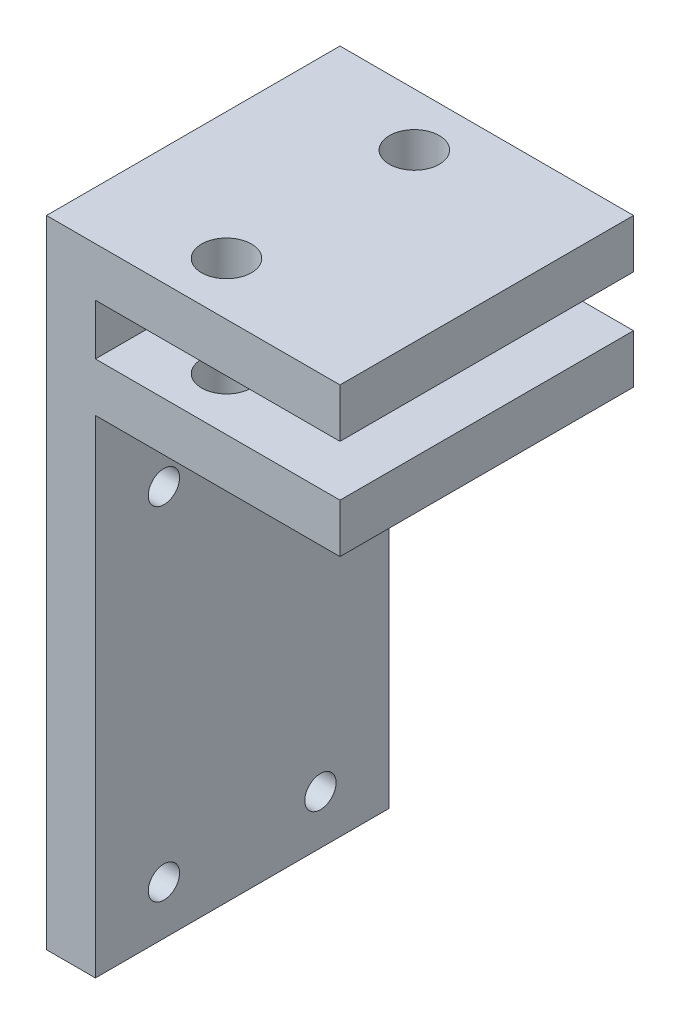
SolidWorks part; units mm, degrees
ref_plane "Front Plane" through (0, 0, 0) normal (0, 0, 1) x (1, 0, 0)
ref_plane "Top Plane" through (0, 0, 0) normal (0, 1, 0) x (1, 0, 0)
ref_plane "Right Plane" through (0, 0, 0) normal (1, 0, 0) x (0, 0, -1)
sketch "Sketch1" plane through (0, 0, 0) normal (0, 0, 1) x (1, 0, 0)
  line L0 (0, 0) -> (0, 5)
  line L1 (0, 5) -> (-30, 5)
  line L2 (-30, 5) -> (-30, -60)
  line L3 (-30, -60) -> (-25, -60)
  line L4 (-25, -60) -> (-25, -10.2)
  line L5 (-25, 0) -> (0, 0)
  line L6 (-25, -5.2) -> (0, -5.2)
  line L7 (0, -5.2) -> (0, -10.2)
  line L8 (0, -10.2) -> (-25, -10.2)
  line L9 (-25, -5.2) -> (-25, 0)
  dimension "D1" = 5
  dimension "D2" = 30
  dimension "D3" = 5
  dimension "60" = 60
  dimension "D5" = 5.2
extrude "Boss-Extrude1" add sketch "Sketch1" along normal blind 30
sketch "Sketch2" plane through (-30, 0, 0) normal (-1, 0, 0) x (0, 0, 1)
  line L0 (0, 0) -> (30, 0) construction
  line L1 (0, 0) -> (30, -60) construction
  line L2 (30, 0) -> (0, -60) construction
  line L3 (30, -60) -> (0, -60) construction
  line L4 (7, -55) -> (23, -55) construction
  line L5 (7, -55) -> (7, -20) construction
  line L6 (7, -20) -> (23, -20) construction
  line L7 (23, -55) -> (23, -20) construction
  line L8 (7, -55) -> (23, -20) construction
  line L9 (7, -20) -> (23, -55) construction
  circle A0 centre (7, -20) radius 1.6
  circle A1 centre (23, -20) radius 1.6
  circle A2 centre (7, -55) radius 1.6
  circle A3 centre (23, -55) radius 1.6
  point P4 (0, 0)
  point P9 (15, -27.5)
  point P18 (15, -30)
  point P19 (0, 0)
  point P20 (15, -31.2953)
  point P21 (7, -10.7945)
  point P28 (15, -37.5)
  dimension "D3" = 3.2
  dimension "D1" = 16
  dimension "D2" = 35
  dimension "D4" = 5
extrude "Cut-Extrude1" cut sketch "Sketch2" against normal up to next
sketch "Sketch3" plane through (0, 5, 0) normal (0, 1, 0) x (1, 0, 0)
  line L0 (-30, -30) -> (-30, 0) construction
  line L1 (-30, 0) -> (-30, -30) construction
  line L2 (0, 0) -> (-30, 0) construction
  line L3 (-30, -15) -> (0, -15) construction
  line L4 (0, -30) -> (0, 0) construction
  circle A0 centre (-17, -5.4) radius 2.55
  circle A1 centre (-17, -24.6) radius 2.55
  point P10 (-30, -15)
  dimension "D2" = 5.1
  dimension "D1" = 13
  dimension "D3" = 5.4
extrude "Cut-Extrude2" cut sketch "Sketch3" against normal through all
